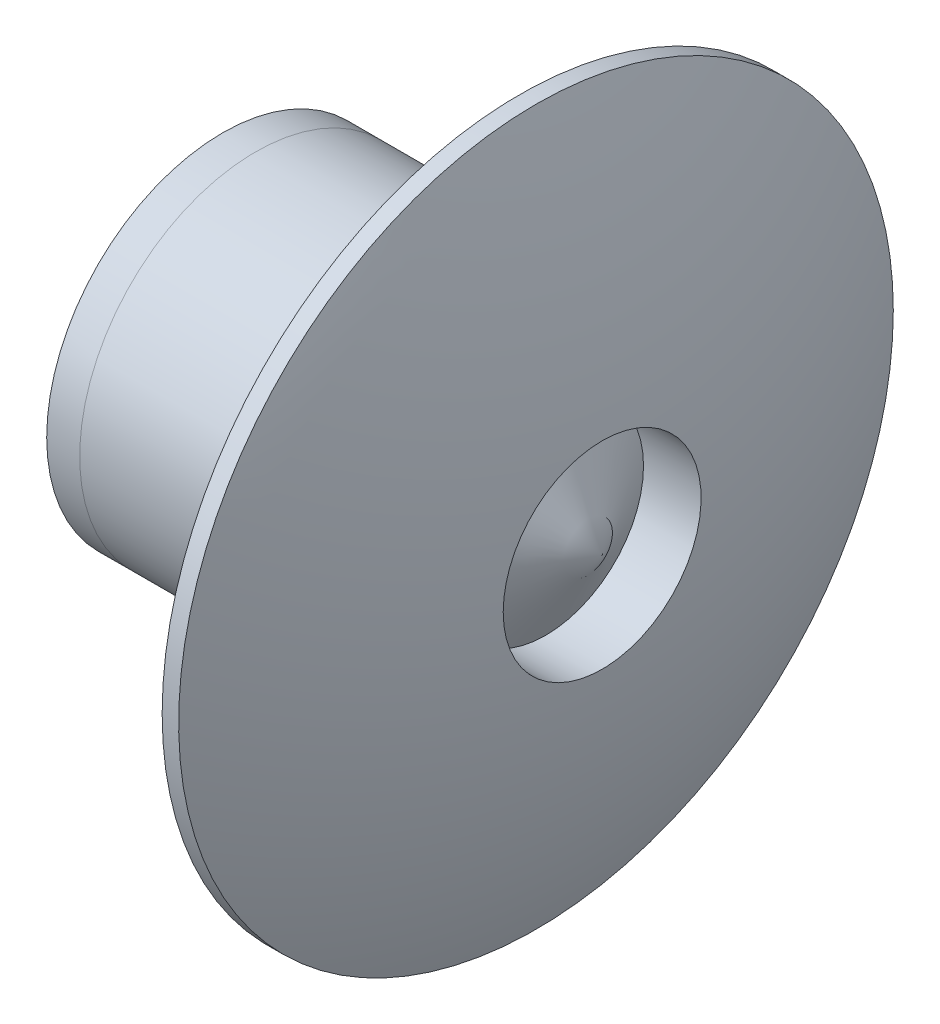
SolidWorks part; units mm, degrees
ref_plane "Front Plane" through (0, 0, 0) normal (0, 0, 1) x (1, 0, 0)
ref_plane "Top Plane" through (0, 0, 0) normal (0, 1, 0) x (1, 0, 0)
ref_plane "Right Plane" through (0, 0, 0) normal (1, 0, 0) x (0, 0, -1)
sketch "Sketch1" plane through (0, 0, 0) normal (0, 0, 1) x (1, 0, 0)
  line L0 (0, 0) -> (-19.4627, 0) construction
  line L1 (0, 3.25) -> (0, 1.6)
  line L2 (0, 1.6) -> (-2.4, 1.6)
  line L3 (-2.4, 1.6) -> (-2.4, 0)
  line L4 (0, 3.25) -> (0.15, 3.25)
  line L5 (0.8, 0) -> (0.8, -2.8558) construction
  line L6 (0.8, 0) -> (0, 0) construction
  line L7 (0.8, 0) -> (-2.4, 0)
  arc A0 (0.15, 3.25) -> (0.8, 0) centre (-7.65, 0) cw
  dimension "D4" = 0.15
  dimension "D1" = 0.8
  dimension "D2" = 2.4
  dimension "D3" = 6.5
  dimension "D5" = 3.2
revolve "Revolve1" add sketch "Sketch1" angle 360 about L0
hole_wizard "Ø1.8 (1.8) Diameter Hole1" positions "Sketch2" profile "Sketch4" hole size "Ø1.8" standard "GB" end condition through all
sketch "Sketch2" plane through (-2.4, 0, 0) normal (-1, 0, 0) x (0, 0, 1)
  point P0 (0, 0)
sketch "Sketch4" plane through (-2.4, 0, 0) normal (0, 1, 0) x (0, 0, 1)
  line L0 (0, 0) -> (0, 3.2)
  line L1 (0, 3.2) -> (0.9, 3.2)
  line L2 (0.9, 3.2) -> (0.9, 0)
  line L5 (0.9, 0) -> (0, 0)
  line L11 (0, -6.35) -> (0, 107.95) construction
  dimension "Thru Hole Dia." = 1.8
  dimension "Thru Hole Depth" = 3.2
chamfer "Chamfer1" distance 0.7 angle 30 1 edges at (-2.4, 0, 0.9)
sketch "Sketch5" plane through (0, 0, 0) normal (0, 0, 1) x (1, 0, 0)
  line L0 (0, 0) -> (-32.0736, 0) construction
  line L1 (0.7519, 0) -> (0.2381, 0.89)
  line L2 (0.2381, 0.89) -> (-1.1702, 0.89)
  line L3 (-1.1702, 0.89) -> (-2.4, 1.6)
  line L4 (-2.4, 1.6) -> (-2.7, 1.6)
  line L5 (-3.1396, 0) -> (-3.1396, 5.2158) construction
  line L7 (0.7519, 0) -> (-3.1396, 0)
  line L8 (0.7519, -0.9) -> (0.7519, 0.9) construction
  line L9 (-2.4, 1.6) -> (-2.4, -1.6) construction
  arc A0 (-2.7, 1.6) -> (-3.1396, 0) centre (-0.0077, 0) ccw
  dimension "D1" = 3.2
  dimension "D2" = 1.78
  dimension "D4" = 0.3
  dimension "D5" = 30
  dimension "D6" = 60
  dimension "D7" = 0
revolve "Revolve2" add sketch "Sketch5" angle 360 about L0
sketch "Sketch6" plane through (0, 0, 0) normal (0, 0, 1) x (1, 0, 0)
  line L0 (-2.4117, 0) -> (-3.5, 0) construction
  line L1 (-3.5, 3.25) -> (-3.5, 1.6)
  line L2 (-3.5, 1.6) -> (-5.5, 1.6)
  line L4 (-3.5, 3.25) -> (-3.35, 3.25)
  line L5 (-9.1179, 0) -> (-2.4117, 0)
  line L6 (-3.5, 0) -> (-3.5, 1.6) construction
  line L9 (-3.5, 0) -> (-19.4627, 0) construction
  line L14 (-5.5, 1.6) -> (-6.128, 3.1549) construction
  line L15 (-6.128, 3.1549) -> (-8.5232, 2.7272) construction
  line L16 (-8.5232, 2.7272) -> (-9.1179, 1.8449) construction
  line L17 (-9.1179, 1.8449) -> (-9.1179, 0) construction
  arc A0 (-3.35, 3.25) -> (-2.4117, 0) centre (-12.351, -1.1091) cw
  spline S0 degree 4 poles (-5.5, 1.6) (-6.128, 3.1549) (-8.5232, 2.7272) (-9.1179, 1.8449) (-9.1179, 0) knots 0 0 0 0 0 1 1 1 1 1
  dimension "D5" = 10.001
  dimension "D7" = 3.2
  dimension "D1" = 6.5
  dimension "D2" = 2
  dimension "D3" = 0.15
revolve "Revolve3" [suppressed] add sketch "Sketch6" angle 360 about L9
hole_wizard "Ø1.8 (1.8) Diameter Hole2" [suppressed] positions "Sketch7" profile "Sketch8" hole size "Ø1.8" standard "BSI"
sketch "Sketch7" plane through (-3.5, 0, 0) normal (-1, 0, 0) x (0, 0, 1)
  point P0 (0, 0)
sketch "Sketch8" plane through (-3.5, 0, 0) normal (0, 1, 0) x (0, 0, 1)
  line L0 (0, 0) -> (0, 1.0883)
  line L1 (0, 1.0883) -> (0.9, 1.0883)
  line L2 (0.9, 1.0883) -> (0.9, 0)
  line L5 (0.9, 0) -> (0, 0)
  line L11 (0, -6.35) -> (0, 107.95) construction
  dimension "Thru Hole Dia." = 1.8
  dimension "Thru Hole Depth" = 1.0883
sketch "Sketch9" [suppressed] plane through (-3.5, 0, 0) normal (-1, 0, 0) x (0, 0, 1)
  circle A0 centre (0, 0) radius 1.6
  dimension "D1" = 3.2
wrap "Wrap1" [suppressed] sketch "Sketch9" source sketch "Sketch9"
